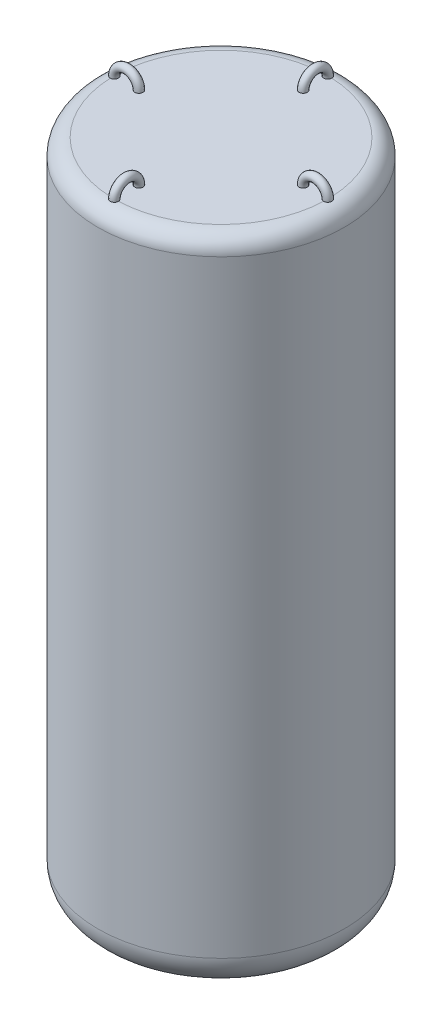
SolidWorks part; units mm, degrees
material "PVC 0.007 Plasticized"
ref_plane "Front Plane" through (0, 0, 0) normal (0, 0, 1) x (1, 0, 0)
ref_plane "Top Plane" through (0, 0, 0) normal (0, 1, 0) x (1, 0, 0)
ref_plane "Right Plane" through (0, 0, 0) normal (1, 0, 0) x (0, 0, -1)
sketch "Sketch1" plane through (0, 0, 0) normal (0, 1, 0) x (1, 0, 0)
  circle A0 centre (0, 0) radius 190.5
  dimension "D1" = 381
extrude "Boss-Extrude1" add sketch "Sketch1" against normal blind 1016
fillet "Fillet1" radius 50.8 1 edges at (0, -1016, 190.5)
fillet "Fillet2" radius 25.4 1 edges at (0, 0, 190.5)
ref_plane "Plane1" through (0, 0, 0) normal (0, 0, 1) x (1, 0, 0)
sketch "Sketch2" plane through (0, 0, 0) normal (0, 1, 0) x (1, 0, 0)
  line L0 (-209.55, 0) -> (209.55, 0) construction
  circle A0 centre (-165.1, 0) radius 6.35
  circle A1 centre (0, 0) radius 165.1 construction
  dimension "D1" = 12.7
sketch "Sketch3" plane through (0, 0, 0) normal (0, 0, 1) x (1, 0, 0)
  line L0 (165.1, 0) -> (-165.1, 0) construction
  line L1 (-165.1, 0) -> (-112.0674, 0) construction
  arc A0 (-127, 0) -> (-165.1, 0) centre (-146.05, 0) ccw
  dimension "D1" = 38.1
sketch "Sketch4" plane through (0, 0, 0) normal (0, 0, 1) x (1, 0, 0)
  line L0 (165.1, 0) -> (-165.1, 0) construction
  line L1 (165.1, 0) -> (0, 0) construction
  arc A0 (165.1, 0) -> (127, 0) centre (146.05, 0) ccw
  dimension "D1" = 38.1
sketch "Sketch5" plane through (0, 0, 0) normal (0, 1, 0) x (1, 0, 0)
  line L0 (165.1, 0) -> (0, 0) construction
  circle A0 centre (165.1, 0) radius 6.35
  circle A1 centre (0, 0) radius 165.1 construction
  dimension "D1" = 12.7
sweep "Sweep1" add profiles "Sketch2" path "Sketch3"
sweep "Sweep2" add profiles "Sketch5" path "Sketch4"
sketch "Sketch6" plane through (0, 0, 0) normal (0, 1, 0) x (1, 0, 0)
  circle A0 centre (0, 165.1) radius 6.35
  arc A1 (164.9779, 6.3488) -> (-164.9779, 6.3488) centre (0, 0) ccw construction
  dimension "D1" = 12.7
sketch "Sketch7" plane through (0, 0, 0) normal (0, 1, 0) x (1, 0, 0)
  circle A0 centre (0, -165.1) radius 6.35
  arc A1 (-164.9779, -6.3488) -> (164.9779, -6.3488) centre (0, 0) ccw construction
  dimension "D1" = 12.7
ref_plane "Plane2" through (0, 0, 0) normal (1, 0, 0) x (0, 0, -1)
sketch "Sketch8" plane through (0, 0, 0) normal (1, 0, 0) x (0, 0, -1)
  line L0 (-6.3488, 0) -> (-165.1, 0) construction
  line L1 (-165.1, 0) -> (0, 0) construction
  arc A0 (-127, 0) -> (-165.1, 0) centre (-146.05, 0) ccw
  dimension "D1" = 38.1
sketch "Sketch9" plane through (0, 0, 0) normal (1, 0, 0) x (0, 0, -1)
  line L0 (165.1, 0) -> (6.3488, 0) construction
  line L1 (165.1, 0) -> (0, 0) construction
  arc A0 (165.1, 0) -> (127, 0) centre (146.05, 0) ccw
  dimension "D1" = 38.1
sweep "Sweep3" add profiles "Sketch7" path "Sketch8"
sweep "Sweep4" add profiles "Sketch6" path "Sketch9"
